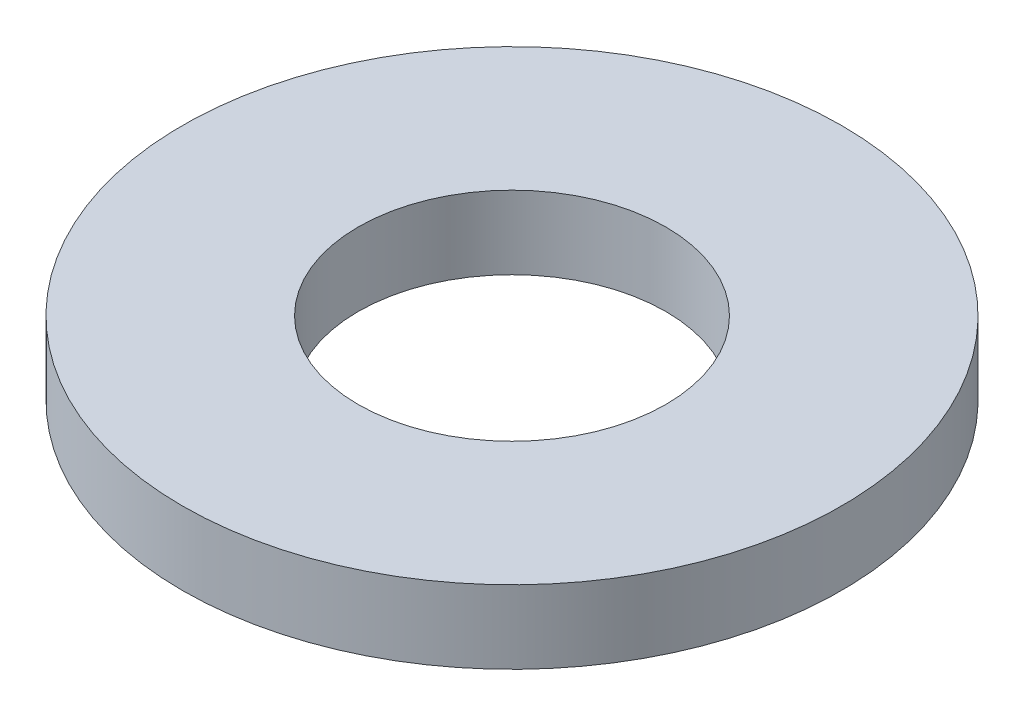
SolidWorks part; units mm, degrees
ref_plane "Front" through (0, 0, 0) normal (0, 0, 1) x (1, 0, 0)
ref_plane "Top" through (0, 0, 0) normal (0, 1, 0) x (1, 0, 0)
ref_plane "Right" through (0, 0, 0) normal (1, 0, 0) x (0, 0, -1)
sketch "Эскиз1" plane through (0, 0, 0) normal (0, 0, 1) x (1, 0, 0)
  line L0 (2.1, 1) -> (4.5, 1)
  line L1 (4.5, 1) -> (4.5, 0)
  line L2 (4.5, 0) -> (2.1, 0)
  line L3 (2.1, 0) -> (2.1, 1)
  line L4 (0, 0) -> (0, 1) construction
  dimension "D1" = 4.5
  dimension "D2" = 2.1
  dimension "D3" = 1
revolve "Повернуть1" add sketch "Эскиз1" angle 360 about L4
